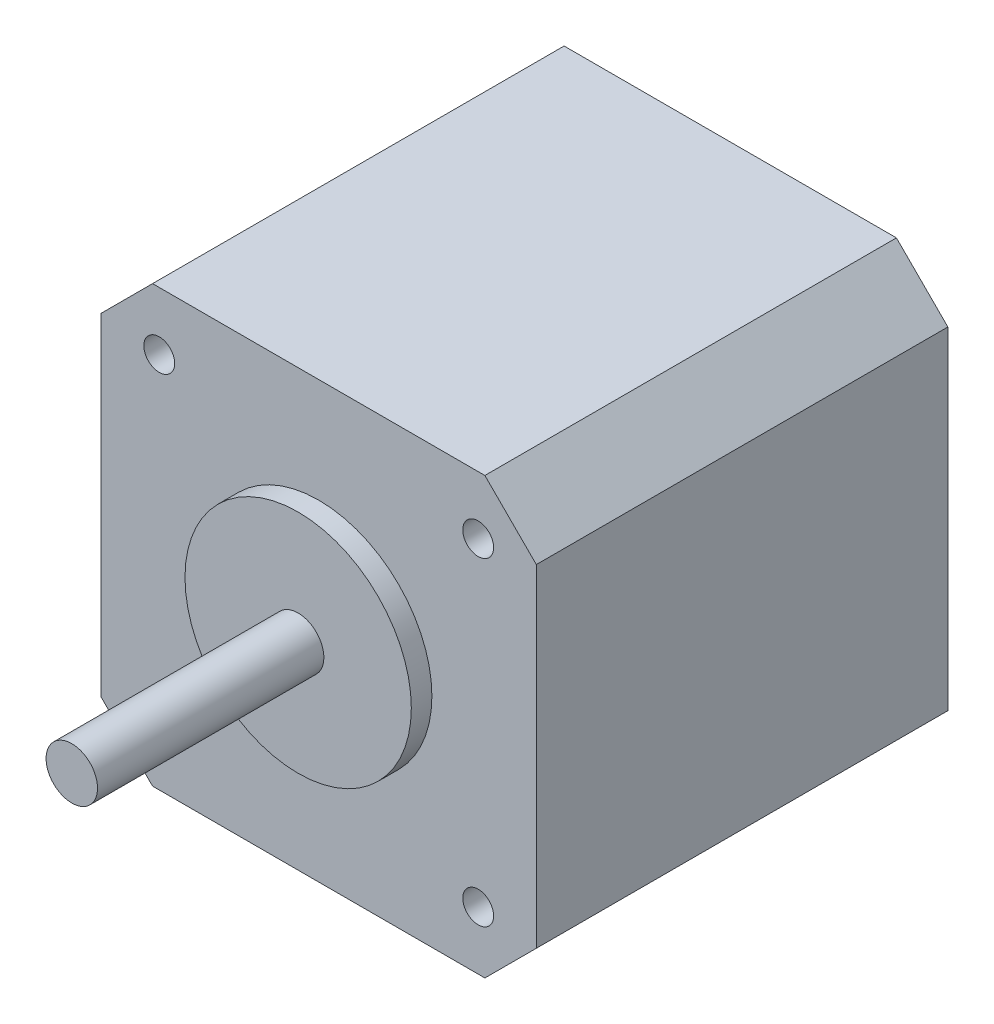
SolidWorks part; units mm, degrees
material "AISI 304"
ref_plane "Спереди" through (0, 0, 0) normal (0, 0, 1) x (1, 0, 0)
ref_plane "Сверху" through (0, 0, 0) normal (0, 1, 0) x (1, 0, 0)
ref_plane "Справа" through (0, 0, 0) normal (1, 0, 0) x (0, 0, -1)
sketch "Sketch1" plane through (0, 0, 0) normal (0, 0, 1) x (1, 0, 0)
  line L1 (-21.15, -21.15) -> (21.15, -21.15)
  line L2 (-21.15, -21.15) -> (-21.15, 21.15)
  line L3 (-21.15, 21.15) -> (21.15, 21.15)
  line L4 (21.15, -21.15) -> (21.15, 21.15)
  point P4 (0, 21.15)
  point P5 (21.15, 0)
  dimension "D1" = 42.3
  dimension "D2" = 42.3
extrude "Boss-Extrude1" add sketch "Sketch1" against normal blind 40
sketch "Sketch2" plane through (0, 0, 0) normal (0, 0, 1) x (1, 0, 0)
  circle A0 centre (0, 0) radius 11
  dimension "D1" = 22
extrude "Boss-Extrude2" add sketch "Sketch2" along normal blind 2
sketch "Sketch3" plane through (0, 0, 2) normal (0, 0, 1) x (1, 0, 0)
  circle A0 centre (0, 0) radius 2.5
  dimension "D1" = 5
extrude "Boss-Extrude3" add sketch "Sketch3" along normal blind 22
sketch "Sketch4" plane through (0, 0, 0) normal (0, 0, 1) x (1, 0, 0)
  circle A0 centre (-15.5, 15.5) radius 1.5
  circle A1 centre (15.5, 15.5) radius 1.5
  circle A2 centre (15.5, -15.5) radius 1.5
  circle A3 centre (-15.5, -15.5) radius 1.5
  dimension "D1" = 3
  dimension "D2" = 31
  dimension "D3" = 31
  dimension "D5" = 15.5
  dimension "D4" = 15.5
extrude "Cut-Extrude1" cut sketch "Sketch4" against normal blind 4.5
chamfer "Chamfer1" distance 5 angle 45 4 edges at (-21.15, -21.15, -20) (21.15, -21.15, -20) (21.15, 21.15, -20) (-21.15, 21.15, -20)
sketch "Sketch5" plane through (0, -21.15, 0) normal (0, -1, 0) x (1, 0, 0)
  line L0 (-16.15, -40) -> (16.15, -40) construction
  line L1 (-2.5, -32) -> (2.5, -32)
  line L2 (-2.5, -32) -> (-2.5, -37)
  line L3 (-2.5, -37) -> (2.5, -37)
  line L4 (2.5, -32) -> (2.5, -37)
  point P4 (0, -32)
  point P7 (0, -40)
  dimension "D1" = 5
  dimension "D2" = 5
  dimension "D3" = 3
extrude "Boss-Extrude4" add sketch "Sketch5" along normal blind 1
